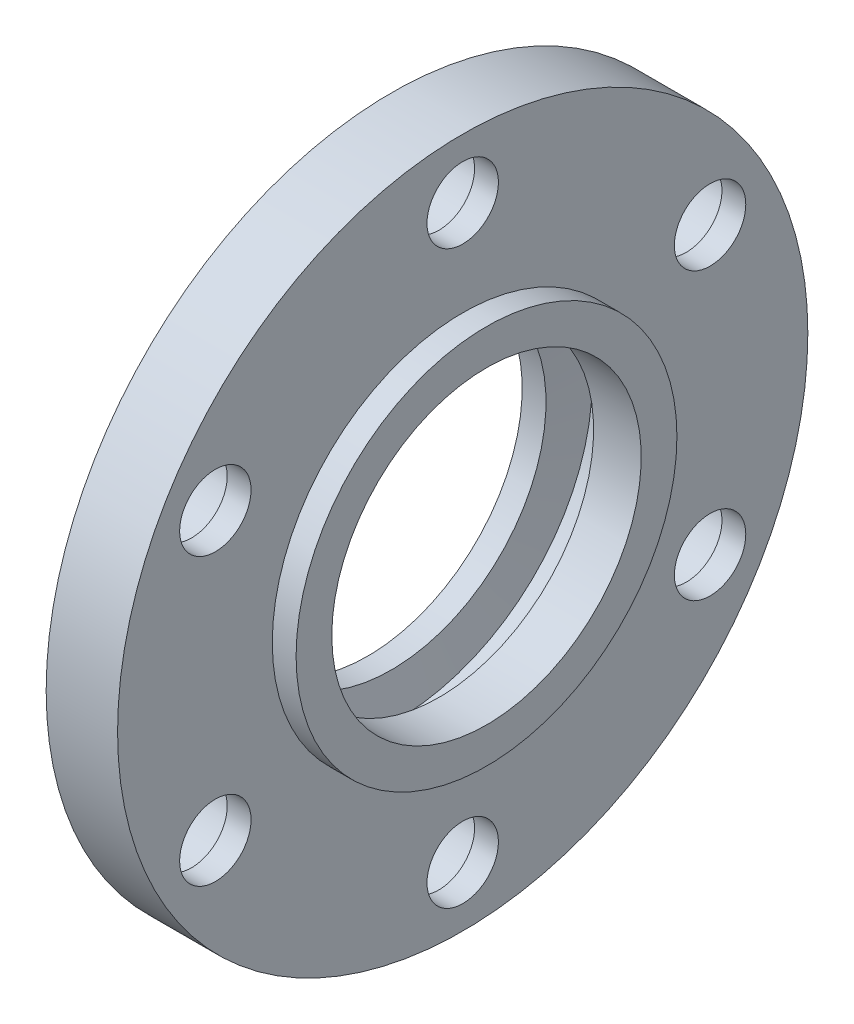
SolidWorks part; units mm, degrees
material "Серое литое железо"
ref_plane "Спереди" through (0, 0, 0) normal (0, 0, 1) x (1, 0, 0)
ref_plane "Сверху" through (0, 0, 0) normal (0, 1, 0) x (1, 0, 0)
ref_plane "Справа" through (0, 0, 0) normal (1, 0, 0) x (0, 0, -1)
sketch "Эскиз1" plane through (0, 0, 0) normal (0, 0, 1) x (1, 0, 0)
  line L0 (2, 29) -> (2, 0)
  line L1 (2, 0) -> (8, 0)
  line L2 (8, 0) -> (8, 29)
  line L3 (8, 29) -> (2, 29)
  line L4 (2, 0) -> (8, 0) construction
revolve "Повернуть1" add sketch "Эскиз1" angle 360 about L4
sketch "Эскиз2" plane through (2, 0, 0) normal (-1, 0, 0) x (0, 0, 1)
  circle A0 centre (0, 0) radius 19.5
extrude "Бобышка-Вытянуть1" add sketch "Эскиз2" along normal blind 2 draft 45
sketch "Эскиз3" plane through (8, 0, 0) normal (1, 0, 0) x (0, 0, -1)
  circle A0 centre (0, 0) radius 16
extrude "Бобышка-Вытянуть2" add sketch "Эскиз3" along normal blind 2
ref_plane "Плоскость4" through (0, 0, 0) normal (0, 0, -1) x (-1, 0, 0)
sketch "Эскиз4" plane through (0, 0, 0) normal (0, 0, -1) x (-1, 0, 0)
  line L0 (-10, 13) -> (-10, 0)
  line L1 (-10, 0) -> (0, 0)
  line L2 (0, 0) -> (0, 13)
  line L3 (0, 13) -> (-2, 13)
  line L4 (-2, 13) -> (-2.5, 16.3736)
  line L5 (-2.5, 16.3736) -> (-5.5, 16.3736)
  line L6 (-5.5, 16.3736) -> (-6, 13)
  line L7 (-6, 13) -> (-10, 13)
  line L8 (-10, 0) -> (0, 0) construction
revolve "Вырез-Повернуть1" cut sketch "Эскиз4" angle 360 about L8
hole_wizard "Отверстие1" positions "Эскиз6" profile "Эскиз5" legacy
sketch "Эскиз6" plane through (2, 0, 0) normal (-1, 0, 0) x (0, 0, 1)
  point P0 (20.7846, -12)
  point P1 (0, -24)
  point P2 (-20.7846, -12)
  point P3 (-20.7846, 12)
  point P4 (0, 24)
  point P5 (20.7846, 12)
sketch "Эскиз5" plane through (2, -12, 20.7846) normal (0, 1, 0) x (0, 0, 1)
  line L0 (0, 0) -> (0, 8)
  line L1 (0, 8) -> (3, 8)
  line L2 (3, 8) -> (3, 4)
  line L3 (3, 4) -> (4.25, 4)
  line L4 (4.25, 4) -> (4.25, 0)
  line L5 (4.25, 0) -> (0, 0)
  line L6 (0, 110) -> (0, -10) construction
  dimension "Диаметр" = 6
  dimension "Глубина" = 8
  dimension "Диа. цековки" = 8.5
  dimension "Глуб. цековки" = 4
